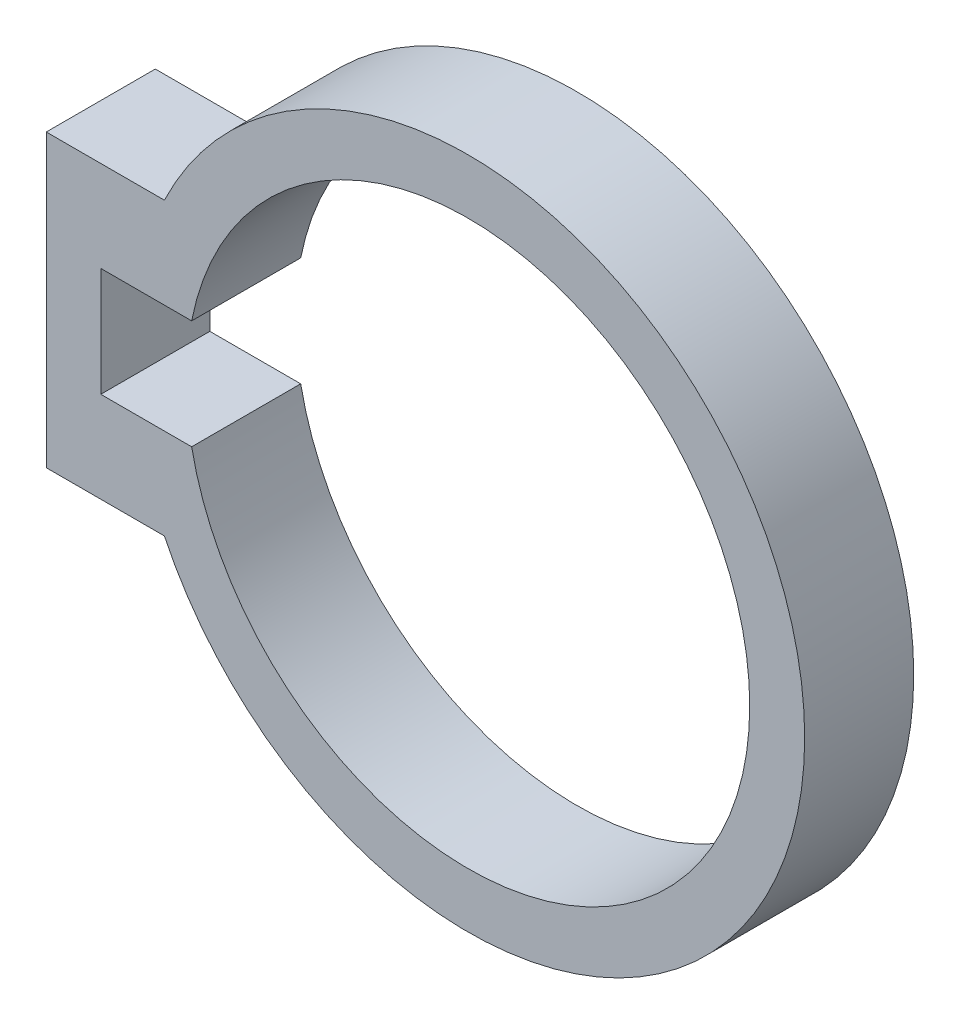
SolidWorks part; units mm, degrees
ref_plane "Plan de face" through (0, 0, 0) normal (0, 0, 1) x (1, 0, 0)
ref_plane "Plan de dessus" through (0, 0, 0) normal (0, 1, 0) x (1, 0, 0)
ref_plane "Plan de droite" through (0, 0, 0) normal (1, 0, 0) x (0, 0, -1)
sketch "Esquisse1" plane through (0, 0, 0) normal (0, 0, 1) x (1, 0, 0)
  line L1 (0, 0) -> (6.5, 0)
  line L3 (3, -5) -> (8, -5)
  line L6 (0, 0) -> (0, -16)
  line L8 (3, -5) -> (3, -11)
  line L9 (0, -16) -> (6.5, -16)
  line L11 (3, -11) -> (8, -11)
  arc A0 (6.5, 0) -> (6.5, -16) centre (23.2069, -8) cw
  arc A1 (8, -5) -> (8, -11) centre (23.2069, -8) cw
  dimension "D4" = 15.5
  dimension "D8" = 5
  dimension "D1" = 5
  dimension "D2" = 6.5
  dimension "D3" = 0
  dimension "D5" = 5
  dimension "D6" = 3
  dimension "D7" = 16
  dimension "D9" = 5
  dimension "D10" = 6.5
extrude "Boss.-Extru.1" add sketch "Esquisse1" along normal blind 6
